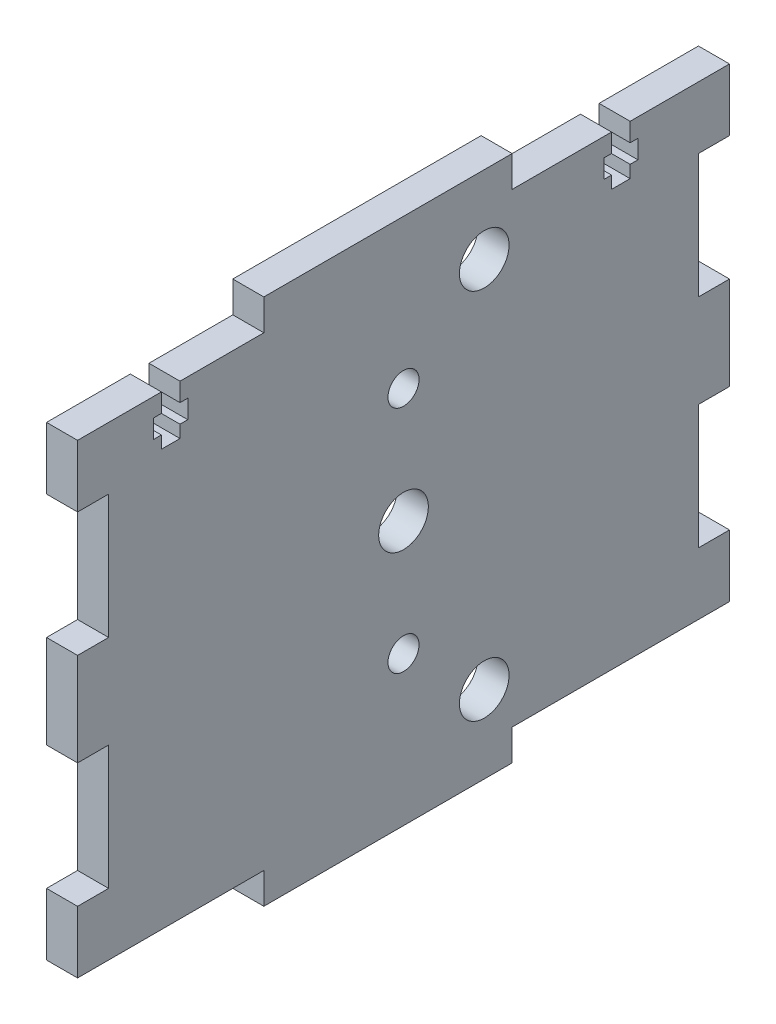
SolidWorks part; units mm, degrees
ref_plane "前视基准面" through (0, 0, 0) normal (0, 0, 1) x (1, 0, 0)
ref_plane "上视基准面" through (0, 0, 0) normal (0, 1, 0) x (1, 0, 0)
ref_plane "右视基准面" through (0, 0, 0) normal (1, 0, 0) x (0, 0, -1)
sketch "草图1" plane through (0, 0, 0) normal (1, 0, 0) x (0, 0, -1)
  line L0 (-62.1274, 56.7878) -> (-75.6274, 56.7878)
  line L1 (12.8726, -18.2122) -> (-22.1274, -18.2122)
  line L2 (12.8726, -18.2122) -> (12.8726, -8.2122)
  line L3 (12.8726, 56.7878) -> (-3.1274, 56.7878)
  line L4 (-92.1274, -18.2122) -> (-92.1274, -8.2122)
  line L5 (-39.6274, 78.2295) -> (-39.6274, -46.8351) construction
  line L6 (-62.1274, -18.2122) -> (-62.1274, -23.2122)
  line L7 (-62.1274, -23.2122) -> (-22.1274, -23.2122)
  line L8 (-22.1274, -18.2122) -> (-22.1274, -23.2122)
  line L9 (-92.1274, 46.7878) -> (-92.1274, 56.7878)
  line L10 (-62.1274, 56.7878) -> (-62.1274, 61.7878)
  line L11 (-62.1274, 61.7878) -> (-22.1274, 61.7878)
  line L12 (-22.1274, 56.7878) -> (-22.1274, 61.7878)
  line L13 (12.8726, 46.7878) -> (7.8726, 46.7878)
  line L14 (-26.6274, 58.8671) -> (-26.6274, -15.1232) construction
  line L15 (12.8726, 26.7878) -> (7.8726, 26.7878)
  line L16 (7.8726, 46.7878) -> (7.8726, 26.7878)
  line L17 (12.8726, 11.7878) -> (7.8726, 11.7878)
  line L18 (12.8726, -8.2122) -> (7.8726, -8.2122)
  line L19 (7.8726, 11.7878) -> (7.8726, -8.2122)
  line L20 (-92.1274, 11.7878) -> (-87.1274, 11.7878)
  line L21 (12.8726, 46.7878) -> (12.8726, 56.7878)
  line L22 (-92.1274, -8.2122) -> (-87.1274, -8.2122)
  line L23 (-87.1274, 11.7878) -> (-87.1274, -8.2122)
  line L24 (-92.1274, 46.7878) -> (-87.1274, 46.7878)
  line L25 (-92.1274, 26.7878) -> (-87.1274, 26.7878)
  line L26 (-87.1274, 46.7878) -> (-87.1274, 26.7878)
  line L27 (-92.1274, 11.7878) -> (-92.1274, 26.7878)
  line L28 (12.8726, 11.7878) -> (12.8726, 26.7878)
  line L29 (-62.1274, -18.2122) -> (-92.1274, -18.2122)
  line L30 (-3.1274, 56.7878) -> (-3.1274, 53.7878)
  line L31 (-3.1274, 53.7878) -> (-1.8774, 53.7878)
  line L32 (-1.8774, 53.7878) -> (-1.8774, 50.7878)
  line L33 (-1.8774, 50.7878) -> (-3.1274, 50.7878)
  line L34 (-3.1274, 50.7878) -> (-3.1274, 48.7878)
  line L35 (-3.1274, 48.7878) -> (-6.1274, 48.7878)
  line L36 (-6.1274, 48.7878) -> (-6.1274, 50.7878)
  line L37 (-6.1274, 50.7878) -> (-7.3774, 50.7878)
  line L38 (-7.3774, 50.7878) -> (-7.3774, 53.7878)
  line L39 (-7.3774, 53.7878) -> (-6.1274, 53.7878)
  line L40 (-6.1274, 53.7878) -> (-6.1274, 56.7878)
  line L41 (-6.1274, 56.7878) -> (-22.1274, 56.7878)
  line L42 (-75.6274, 56.7878) -> (-75.6274, 53.7878)
  line L43 (-75.6274, 53.7878) -> (-74.3774, 53.7878)
  line L44 (-74.3774, 53.7878) -> (-74.3774, 50.7878)
  line L45 (-74.3774, 50.7878) -> (-75.6274, 50.7878)
  line L46 (-75.6274, 50.7878) -> (-75.6274, 48.7878)
  line L47 (-75.6274, 48.7878) -> (-78.6274, 48.7878)
  line L48 (-78.6274, 48.7878) -> (-78.6274, 50.7878)
  line L49 (-78.6274, 50.7878) -> (-79.8774, 50.7878)
  line L50 (-79.8774, 50.7878) -> (-79.8774, 53.7878)
  line L51 (-79.8774, 53.7878) -> (-78.6274, 53.7878)
  line L52 (-78.6274, 53.7878) -> (-78.6274, 56.7878)
  line L53 (-78.6274, 56.7878) -> (-92.1274, 56.7878)
  circle A0 centre (-39.6274, 19.2878) radius 4
  circle A1 centre (-39.6274, 37.7878) radius 2.5
  circle A2 centre (-39.6274, 0.7878) radius 2.5
  circle A5 centre (-26.6274, 49.2878) radius 4
  circle A6 centre (-26.6274, -10.7122) radius 4
  dimension "D28" = 3
  dimension "D35" = 8
  dimension "D36" = 8
  dimension "D21" = 8
  dimension "D22" = 5
  dimension "D23" = 5
  dimension "D1" = 105
  dimension "D2" = 75
  dimension "D3" = 40
  dimension "D4" = 40
  dimension "D5" = 5
  dimension "D6" = 5
  dimension "D7" = 5
  dimension "D8" = 5
  dimension "D9" = 5
  dimension "D10" = 5
  dimension "D11" = 20
  dimension "D12" = 20
  dimension "D13" = 20
  dimension "D14" = 20
  dimension "D15" = 35
  dimension "D16" = 35
  dimension "D17" = 10
  dimension "D18" = 10
  dimension "D19" = 10
  dimension "D20" = 10
  dimension "D24" = 37
  dimension "D25" = 18.5
  dimension "D26" = 3
  dimension "D27" = 5.5
  dimension "D29" = 52.5
  dimension "D30" = 0
  dimension "D31" = 1.25
  dimension "D32" = 1.25
  dimension "D33" = 37.5
  dimension "D34" = 13
  dimension "D37" = 60
  dimension "D38" = 7.5
  dimension "D39" = 16
  dimension "D40" = 3
  dimension "D41" = 5.5
  dimension "D42" = 3
  dimension "D43" = 1.25
  dimension "D44" = 1.25
  dimension "D45" = 13.5
extrude "凸台-拉伸1" add sketch "草图1" along normal blind 5
